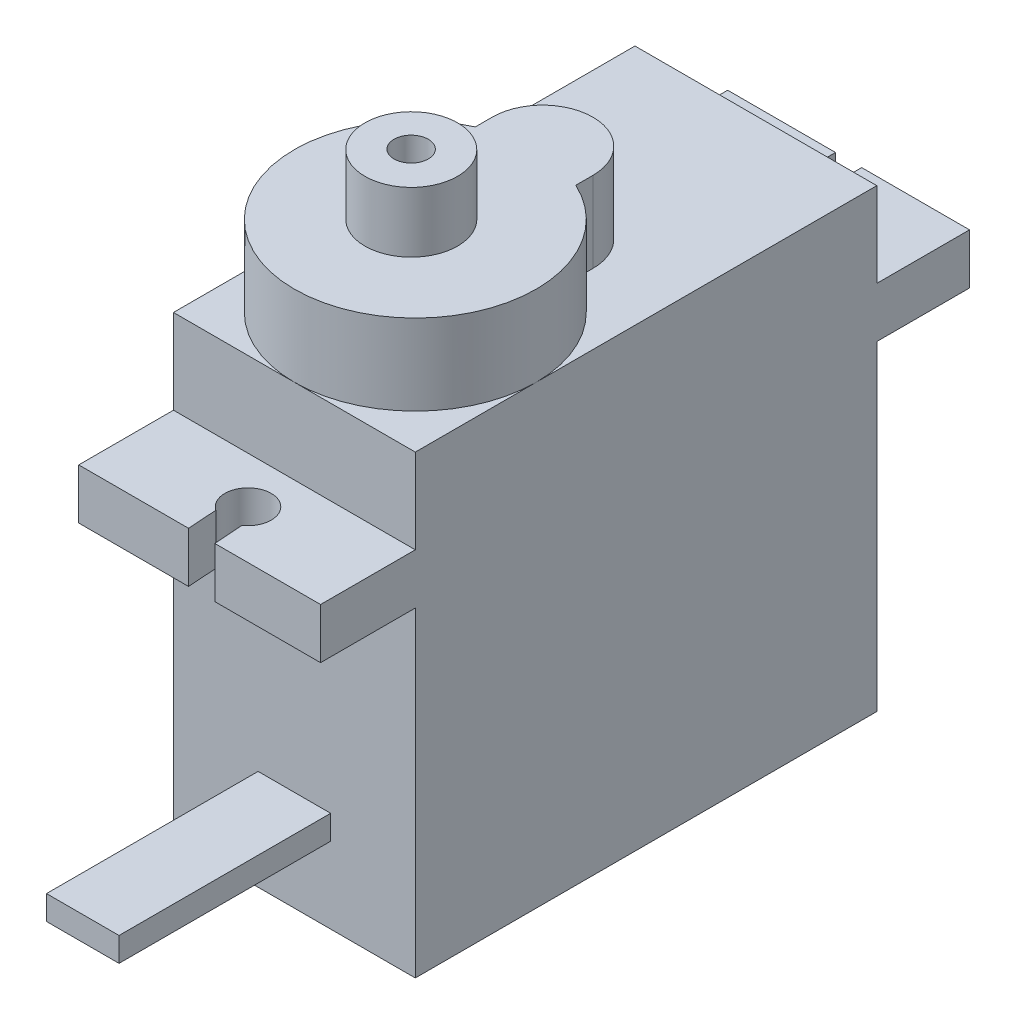
SolidWorks part; units mm, degrees
ref_plane "Front Plane" through (0, 0, 0) normal (0, 0, 1) x (1, 0, 0)
ref_plane "Top Plane" through (0, 0, 0) normal (0, 1, 0) x (1, 0, 0)
ref_plane "Right Plane" through (0, 0, 0) normal (1, 0, 0) x (0, 0, -1)
sketch "Sketch2" plane through (0, 0, 0) normal (0, 1, 0) x (1, 0, 0)
  line L1 (0, 0) -> (12, 0)
  line L2 (0, 0) -> (0, 22.9)
  line L3 (0, 22.9) -> (12, 22.9)
  line L4 (12, 0) -> (12, 22.9)
  dimension "D1" = 12
  dimension "D2" = 22.9
extrude "Boss-Extrude1" add sketch "Sketch2" along normal blind 22.6
ref_plane "Plane1" through (0, 0, 4.7) normal (0, 0, 1) x (1, 0, 0)
sketch "Sketch3" plane through (0, 0, 4.7) normal (0, 0, 1) x (1, 0, 0)
  line L0 (0, 22.6) -> (0, 0) construction
  line L1 (0, 18.4) -> (12, 18.4)
  line L2 (0, 18.4) -> (0, 15.9)
  line L3 (0, 15.9) -> (12, 15.9)
  line L4 (12, 18.4) -> (12, 15.9)
  line L5 (12, 22.6) -> (12, 0) construction
  line L6 (0, 0) -> (12, 0) construction
  dimension "D1" = 2.5
  dimension "D2" = 15.9
extrude "Boss-Extrude2" add sketch "Sketch3" against normal blind 32.2
sketch "Sketch5" plane through (0, 22.6, 0) normal (0, 1, 0) x (1, 0, 0)
  line L0 (0, 0) -> (12, 0) construction
  line L1 (3.515, 12.3) -> (3.515, 11.4612)
  line L2 (8.515, 12.3) -> (8.515, 11.4474)
  line L3 (12, 0) -> (12, 22.9) construction
  line L4 (0, 22.9) -> (0, 0) construction
  arc A0 (3.515, 11.4612) -> (8.515, 11.4474) centre (6, 6) ccw
  arc A1 (8.515, 12.3) -> (3.515, 12.3) centre (6.015, 12.3) ccw
  dimension "D1" = 5
  dimension "D2" = 6.3
extrude "Boss-Extrude3" add sketch "Sketch5" along normal blind 4
sketch "Sketch7" plane through (0, 26.6, 0) normal (0, 1, 0) x (1, 0, 0)
  circle A1 centre (5.9, 5.9) radius 2.3
  dimension "D1" = 4.6
extrude "Boss-Extrude4" add sketch "Sketch7" along normal blind 3
sketch "Sketch9" plane through (0, 18.4, 0) normal (0, 1, 0) x (1, 0, 0)
  line L0 (5.35, 27.5) -> (6.65, 27.5)
  line L1 (12, 22.9) -> (12, 0) construction
  line L2 (6, 27.5) -> (6, 30.3648) construction
  line L3 (12, 27.5) -> (0, 27.5) construction
  line L4 (12, 11.45) -> (-3.7052, 11.45) construction
  line L5 (6.75, -4.7) -> (6.65, -3.2487)
  line L6 (12, -4.7) -> (0, -4.7) construction
  line L7 (5.45, -4.7) -> (5.35, -3.2487)
  line L8 (0, 27.5) -> (0, 22.9) construction
  line L9 (5.35, 27.5) -> (5.35, 26.1487)
  line L10 (6.65, 27.5) -> (6.65, 26.1487)
  line L11 (5.45, -4.7) -> (6.75, -4.7)
  arc A0 (5.35, 26.1487) -> (6.65, 26.1487) centre (6, 25.2) ccw
  arc A1 (5.35, -3.2487) -> (6.65, -3.2487) centre (6, -2.3) cw
  dimension "D1" = 6
  dimension "D2" = 2.3
  dimension "D3" = 2.3
  dimension "D4" = 1.3
  dimension "D5" = 0.65
extrude "Cut-Extrude1" cut sketch "Sketch9" against normal blind 2.5
sketch "Sketch10" plane through (0, 29.6, 0) normal (0, 1, 0) x (1, 0, 0)
  circle A1 centre (5.8781, 5.9162) radius 0.85
  dimension "D1" = 1.7
extrude "Cut-Extrude2" cut sketch "Sketch10" against normal blind 2.5
sketch "Sketch12" plane through (0, 0, 0) normal (0, 0, 1) x (1, 0, 0)
  line L1 (4.2, 4.978) -> (7.8, 4.978)
  line L2 (4.2, 4.978) -> (4.2, 3.778)
  line L3 (4.2, 3.778) -> (7.8, 3.778)
  line L4 (7.8, 4.978) -> (7.8, 3.778)
  line L5 (6, 0) -> (6, 7.2512) construction
  line L6 (0, 0) -> (12, 0) construction
  dimension "D1" = 3.6
  dimension "D2" = 1.2
  dimension "D3" = 1.8
extrude "Boss-Extrude5" add sketch "Sketch12" along normal blind 10.5
